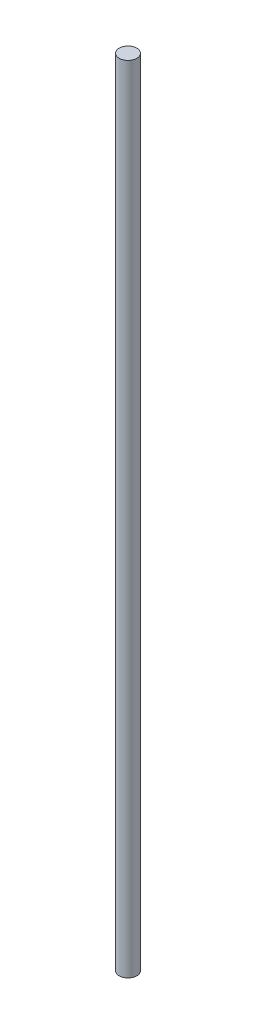
SolidWorks part; units mm, degrees
ref_plane "Plan de face" through (0, 0, 0) normal (0, 0, 1) x (1, 0, 0)
ref_plane "Plan de dessus" through (0, 0, 0) normal (0, 1, 0) x (1, 0, 0)
ref_plane "Plan de droite" through (0, 0, 0) normal (1, 0, 0) x (0, 0, -1)
sketch "Esquisse1" plane through (0, 0, 0) normal (0, 0, 1) x (1, 0, 0)
  line L0 (3, 270) -> (0, 270)
  line L1 (0, 270) -> (0, 0)
  line L2 (0, 0) -> (3, 0)
  line L3 (3, 0) -> (3, 270)
  line L4 (0, 270) -> (0, 0) construction
  dimension "D1" = 270
revolve "Révolution1" add sketch "Esquisse1" angle 360 about L4
